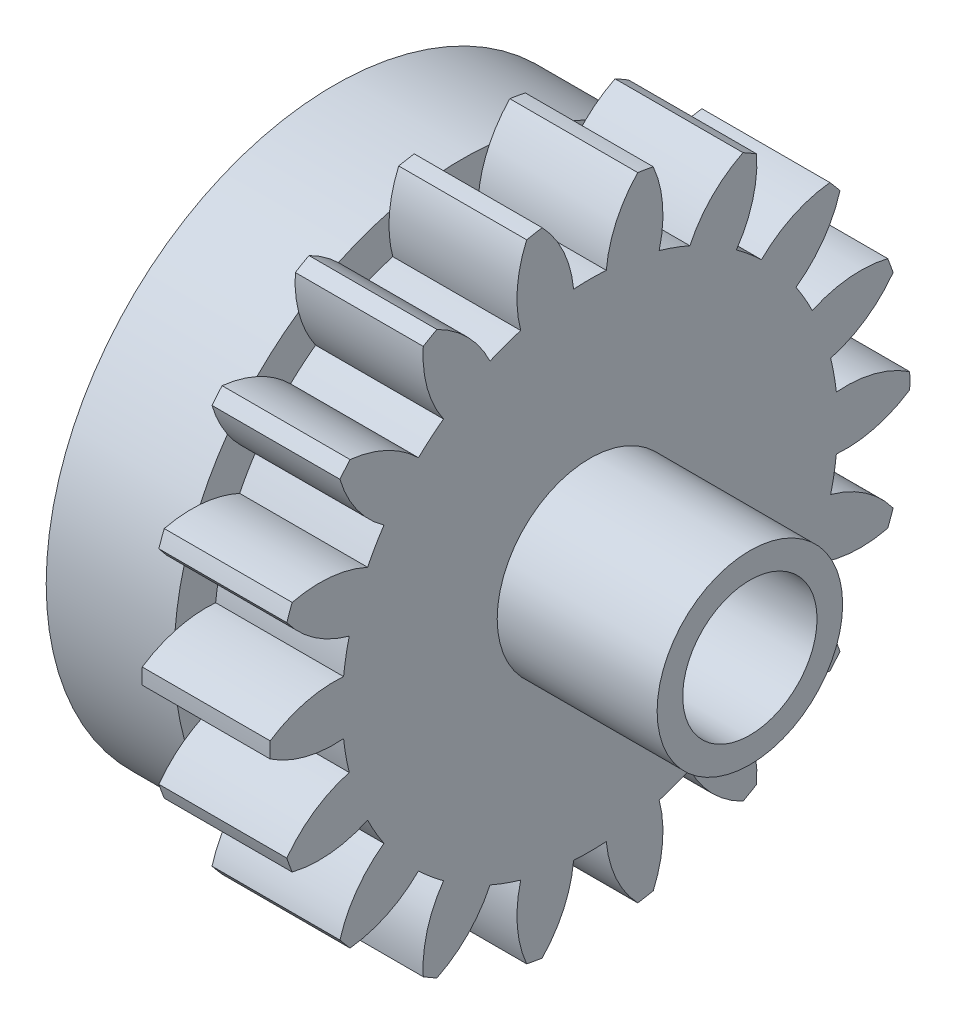
SolidWorks part; units mm, degrees
ref_plane "Plane1" through (0, 0, 0) normal (0, 0, 1) x (1, 0, 0)
ref_plane "Plane2" through (0, 0, 0) normal (0, 1, 0) x (1, 0, 0)
ref_plane "Plane3" through (0, 0, 0) normal (1, 0, 0) x (0, 0, -1)
other "Configuration Table"
sketch "HoldingSke" plane through (0, 0, 0) normal (0, 1, 0) x (1, 0, 0)
  line L0 (0, 0) -> (0.9511, -0.309)
  line L1 (-15, 0) -> (100, 0) construction
  line L2 (0, 0) -> (-2.1039, 2.3779)
  line L3 (0, 0) -> (-11.863, 4.5341)
  line L4 (0, 0) -> (8.2133, 2.6687)
  line L5 (0, 0) -> (-46.8476, -17.4728)
  line L6 (0, 0) -> (-3.3159, -2.2372)
  line L7 (-2.1039, 2.3779) -> (8.6586, 51.2059)
  line L8 (-76.2, 54.61) -> (-75.5, 54.61)
  line L9 (-71.009, 38.7566) -> (-53.1078, 45.2721)
  line L10 (-76.2, 71.12) -> (104.1128, 71.12)
  line L11 (0, 0) -> (-4, 0)
  line L12 (-76.2, 101.6) -> (-76.162, 101.6)
  line L13 (24.9733, 27.94) -> (52.9518, 28.4284)
  line L14 (24.9733, 27.94) -> (24.9743, 27.94)
  line L15 (24.9733, 27.94) -> (100.4006, 29.5858)
  line L16 (-63.627, -1) -> (-12.827, -1)
  circle A0 centre (0, 0) radius 2
  circle A1 centre (0, 0) radius 7.749
  circle A2 centre (0, 0) radius 37.5
  circle A3 centre (0, 0) radius 2
  dimension "MHD" = 15.498
  dimension "Hub_dia" = 75
  dimension "Bore" = 4
  dimension "MBD" = 4
  dimension "Num_teeth" = 18
  dimension "Pitch" = 1
  dimension "Overall_len" = 50
  dimension "Show_teeth" = 18
  dimension "Thickness" = 4
  dimension "OAL" = 50.0001
  dimension "T_dim" = 0.7
  dimension "Ap" = 20
  dimension "H" = 19.05
  dimension "Pitch_radius" = 180.3128
  dimension "Width" = 4
  dimension "Backlash" = 0.038
  dimension "Addendum_fac" = 1
  dimension "Dedendum_fac" = 1.25
  dimension "Clearance_fac" = 0.25
  dimension "Dedendum_add" = 0.001
  dimension "Module" = 1
sketch "BasProSke" plane through (0, 0, 0) normal (0, 1, 0) x (1, 0, 0)
  line L0 (-10, 0) -> (60, 0) construction
  line L1 (0, 0) -> (0, 10)
  line L2 (0, 0) -> (4, 0)
  line L3 (4, 0) -> (4, 10)
  line L4 (4, 10) -> (0, 10)
  dimension "Thickness" = 4
  dimension "Diameter" = 20
revolve "Base-Revolve" add sketch "BasProSke" angle 360 about L0
sketch "TooCutSke" plane through (0, 0, 0) normal (1, 0, 0) x (0, 0, -1)
  line L1 (0, 0) -> (0, 107) construction
  line L2 (0, 0) -> (-0.8509, 8.9597) construction
  line L3 (0, 0) -> (-3.1157, 17.6701) construction
  line L4 (-0.8509, 8.9597) -> (-1.5579, 8.835) construction
  arc A0 (0.5106, 7.7322) -> (-0.5106, 7.7322) centre (0, 0) ccw
  arc A1 (1.5152, 9.9102) -> (-1.5152, 9.9102) centre (0, 0) ccw
  circle A2 centre (0, 0) radius 9 construction
  circle A3 centre (0, 0) radius 8.4572 construction
  arc A4 (-0.5106, 7.7322) -> (-1.5152, 9.9102) centre (-4.0952, 7.3996) ccw
  arc A5 (1.5152, 9.9102) -> (0.5106, 7.7322) centre (4.0952, 7.3996) ccw
  dimension "Root_dia" = 15.498
  dimension "Overcut_dia" = 20.0508
  dimension "Pitch_dia" = 18
  dimension "Base_dia" = 16.9145
  dimension "Flank_rad" = 3.6
  dimension "Half_ang" = 10
  dimension "Half_CT" = 0.7179
extrude "ToothCut" cut sketch "TooCutSke" along normal through all
fillet "Breaks" [suppressed] radius 0.02
fillet "RootFillets" [suppressed] radius 0.251
pattern_circular "TeethCuts" count 18 every 20 about axis through (-10, 0, 0) along (1, 0, 0) of "ToothCut", "RootFillets", "Breaks"
sketch "HubNeaOneSke" plane through (0, 0, 0) normal (-1, 0, 0) x (0, 0, 1)
  circle A0 centre (0, 0) radius 7.749
  dimension "Diameter" = 15.498
extrude "HubNearOne" [suppressed] add sketch "HubNeaOneSke" along normal blind 46.0001
sketch "HubNeaBotSke" plane through (0, 0, 0) normal (-1, 0, 0) x (0, 0, 1)
  circle A0 centre (0, 0) radius 7.749
  dimension "Diameter" = 15.498
extrude "HubNearBoth" [suppressed] add sketch "HubNeaBotSke" along normal blind 23
ref_plane "FarPln" through (4, 0, 0) normal (1, 0, 0) x (0, 0, -1)
sketch "HubFarSke" plane through (4, 0, 0) normal (1, 0, 0) x (0, 0, -1)
  circle A0 centre (0, 0) radius 7.749
  dimension "Diameter" = 15.498
extrude "HubFar" [suppressed] add sketch "HubFarSke" along normal blind 23
sketch "BorSke" plane through (0, 0, 0) normal (1, 0, 0) x (0, 0, -1)
  circle A0 centre (0, 0) radius 2
  dimension "Diameter" = 4
extrude "Bore" cut sketch "BorSke" along normal mid plane 100.0001
sketch "KeySke" plane through (0, 0, 0) normal (1, 0, 0) x (0, 0, -1)
  line L0 (-0.8, 0) -> (-0.8, 2.7)
  line L1 (-0.8, 2.7) -> (0.8, 2.7)
  line L2 (0.8, 2.7) -> (0.8, 0)
  line L3 (0, 0) -> (0, 34) construction
  line L4 (-0.8, 0) -> (0.8, 0)
  dimension "Offset" = 2.7
  dimension "Width" = 1.6
extrude "Keyway" [suppressed] cut sketch "KeySke" along normal mid plane 100.0001
pattern_circular "Keyway2" [suppressed] count 2 every 90 about axis through (-10, 0, 0) along (1, 0, 0)
sketch "草图1" plane through (0, 0, 0) normal (-1, 0, 0) x (0, 0, 1)
  circle A0 centre (0, 0) radius 9
  dimension "D1" = 18
extrude "凸台-拉伸1" add sketch "草图1" along normal blind 4
sketch "草图2" plane through (-4, 0, 0) normal (-1, 0, 0) x (0, 0, 1)
  circle A0 centre (0, 0) radius 2
  dimension "D1" = 4
extrude "切除-拉伸1" cut sketch "草图2" against normal through all
sketch "草图3" plane through (-4, 0, 0) normal (-1, 0, 0) x (0, 0, 1)
  line L1 (6.2, 3.5796) -> (0, 7.1591)
  line L2 (0, 7.1591) -> (-6.2, 3.5796)
  line L3 (-6.2, 3.5796) -> (-6.2, -3.5796)
  line L4 (-6.2, -3.5796) -> (0, -7.1591)
  line L5 (0, -7.1591) -> (6.2, -3.5796)
  line L6 (6.2, -3.5796) -> (6.2, 3.5796)
  circle A0 centre (0, 0) radius 6.2 construction
  dimension "D1" = 12.4
extrude "切除-拉伸2" cut sketch "草图3" against normal blind 3
sketch "草图4" plane through (4, 0, 0) normal (1, 0, 0) x (0, 0, -1)
  point P0 (0, 0)
sketch "草图6" plane through (4, 0, 0) normal (1, 0, 0) x (0, 0, -1)
  circle A0 centre (0, 0) radius 2.9
  dimension "D1" = 5.8
extrude "凸台-拉伸2" add sketch "草图6" along normal blind 5
sketch "草图7" plane through (9, 0, 0) normal (1, 0, 0) x (0, 0, -1)
  circle A0 centre (0, 0) radius 2.1
  dimension "D1" = 4.2
extrude "切除-拉伸3" cut sketch "草图7" against normal through all
equation "' \"Module@HoldingSke\" = 6.35"
equation "' \"Num_teeth@HoldingSke\" = 12"
equation "' \"Ap@HoldingSke\" =  20"
equation "' \"Ap@HoldingSke\" = 20"
equation "' \"Width@HoldingSke\" = 0.5 * 25.4"
equation "' \"Hub_dia@HoldingSke\"= 1 * 25.4"
equation "' \"Hub_dia@HoldingSke\" = 1 * 25.4"
equation "' \"Overall_len@HoldingSke\" = 1.0 * 25.4"
equation "' \"Bore@HoldingSke\" = 0.75 * 25.4"
equation "' \"T_dim@HoldingSke\" = 0.1 * 25.4"
equation "' \"Width@KeySke\" = 0.25 * 25.4"
equation "' \"Show_teeth@HoldingSke\" = 13"
equation "' \"Backlash@HoldingSke\" = 0.009 * 25.4"
equation "' \"Addendum_fac@HoldingSke\" = 1.0"
equation "' \"Dedendum_fac@HoldingSke\" = 1.25"
equation "' \"Dedendum_add@HoldingSke\" = 0.00005 * 25.4"
equation "' \"Clearance_fac@HoldingSke\" = 0.25"
equation "\"Pitch@HoldingSke\" = 1 / \"Module@HoldingSke\""
equation "\"Overcut_dia@TooCutSke\" = (\"Num_teeth@HoldingSke\" + 2 * \"Addendum_fac@HoldingSke\") / \"Pitch@HoldingSke\" + 0.002 * 25.4"
equation "\"Pitch_dia@TooCutSke\" = \"Num_teeth@HoldingSke\" / \"Pitch@HoldingSke\""
equation "\"Base_dia@TooCutSke\" = \"Num_teeth@HoldingSke\" / \"Pitch@HoldingSke\" * cos((\"Ap@HoldingSke\"  * 3.14159265 / 180))"
equation "\"Root_dia@TooCutSke\" = (\"Num_teeth@HoldingSke\" + 2) / \"Pitch@HoldingSke\" - 2 * (\"Addendum_fac@HoldingSke\" + \"Dedendum_fac@HoldingSke\") / \"Pitch@HoldingSke\" - \"Dedendum_add@HoldingSke\" * 2"
equation "\"Half_ang@TooCutSke\" = 180 / \"Num_teeth@HoldingSke\""
equation "\"Half_CT@TooCutSke\" = \"Num_teeth@HoldingSke\" / \"Pitch@HoldingSke\" * sin((3.14159265 / 2 / \"Num_teeth@HoldingSke\")) / 2 - 7 * \"Backlash@HoldingSke\" / 4"
equation "\"Flank_rad@TooCutSke\" = \"Num_teeth@HoldingSke\" / \"Pitch@HoldingSke\" / 5"
equation "\"Radius@RootFillets\" = \"Clearance_fac@HoldingSke\" / \"Pitch@HoldingSke\" + \"Dedendum_add@HoldingSke\""
equation "\"Break_rad@Breaks\" = 0.02 / \"Pitch@HoldingSke\""
equation "\"Thickness@HoldingSke\" = \"Width@HoldingSke\""
equation "\"OAL@HoldingSke\" = \"Thickness@HoldingSke\""
equation "\"MHD@HoldingSke\" = (\"Num_teeth@HoldingSke\" + 2) / \"Pitch@HoldingSke\" - 2 * (\"Addendum_fac@HoldingSke\" + \"Dedendum_fac@HoldingSke\")  / \"Pitch@HoldingSke\" - \"Dedendum_add@HoldingSke\" * 2"
equation "\"MBD@HoldingSke\" = (\"Num_teeth@HoldingSke\" + 2) / \"Pitch@HoldingSke\" - 2 * (\"Addendum_fac@HoldingSke\" + \"Dedendum_fac@HoldingSke\")  / \"Pitch@HoldingSke\" - \"Dedendum_add@HoldingSke\" * 2 - 0.002 * 25.4"
equation "\"MHD@HoldingSke\" = ((sgn( \"MHD@HoldingSke\" - \"Hub_dia@HoldingSke\" )-1)*( \"MHD@HoldingSke\" - \"Hub_dia@HoldingSke\" ))/-2+ \"Hub_dia@HoldingSke\""
equation "\"MBD@HoldingSke\" = ((sgn( \"MBD@HoldingSke\" - \"Bore@HoldingSke\" )-1)*( \"MBD@HoldingSke\" - \"Bore@HoldingSke\" ))/-2+ \"Bore@HoldingSke\""
equation "\"OAL@HoldingSke\" = ((sgn( \"OAL@HoldingSke\" - \"Overall_len@HoldingSke\" )+1)*( \"OAL@HoldingSke\" - \"Overall_len@HoldingSke\" ))/2 + \"Overall_len@HoldingSke\" + 0.000002 * 25.4"
equation "\"Num_teeth@TeethCuts\" = int( \"Show_teeth@HoldingSke\" ) + 1"
equation "\"Num_teeth@TeethCuts\" = ((sgn( \"Num_teeth@TeethCuts\" - \"Num_teeth@HoldingSke\" )-1)*( \"Num_teeth@TeethCuts\" - \"Num_teeth@HoldingSke\" ))/-2+ \"Num_teeth@HoldingSke\""
equation "\"Num_teeth@TeethCuts\" = ((sgn( \"Num_teeth@TeethCuts\" - 2.0)+1)*( \"Num_teeth@TeethCuts\" - 2.0))/2 +2.0"
equation "\"Angle@TeethCuts\" = 360.0 / \"Num_teeth@HoldingSke\""
equation "\"Diameter@BasProSke\" = (\"Num_teeth@HoldingSke\" + 2 * \"Addendum_fac@HoldingSke\") / \"Pitch@HoldingSke\""
equation "\"Thickness@BasProSke\"  = \"Thickness@HoldingSke\""
equation "' \"Fillet_rad@BasProSke\" =  \"Thickness@HoldingSke\" * 0.05"
equation "' \"Fillet_rad@BasProSke\" = \"Thickness@HoldingSke\" * 0.05"
equation "\"MHD@HoldingSke\" = ((sgn( \"MHD@HoldingSke\" - \"Root_dia@TooCutSke\" )-1)*( \"MHD@HoldingSke\" - \"Root_dia@TooCutSke\" ))/-2+ \"Root_dia@TooCutSke\""
equation "\"Diameter@HubNeaOneSke\" = \"MHD@HoldingSke\""
equation "\"Length@HubNearOne\" = \"OAL@HoldingSke\" - \"Thickness@BasProSke\""
equation "\"Diameter@HubNeaBotSke\" = \"MHD@HoldingSke\""
equation "\"Length@HubNearBoth\" = ( \"OAL@HoldingSke\" - \"Thickness@BasProSke\" ) / 2.0"
equation "\"Thickness@FarPln\" = \"Thickness@BasProSke\""
equation "\"Diameter@HubFarSke\" = \"MHD@HoldingSke\""
equation "\"Length@HubFar\" = ( \"OAL@HoldingSke\" - \"Thickness@BasProSke\" ) / 2.0"
equation "\"Diameter@BorSke\" = \"MBD@HoldingSke\""
equation "\"D1@Bore\" = \"OAL@HoldingSke\" * 2.0"
equation "\"D1@Keyway\" = \"OAL@HoldingSke\" * 2.0"
equation "\"Offset@KeySke\" = \"T_dim@HoldingSke\" + \"MBD@HoldingSke\" / 2.0"
